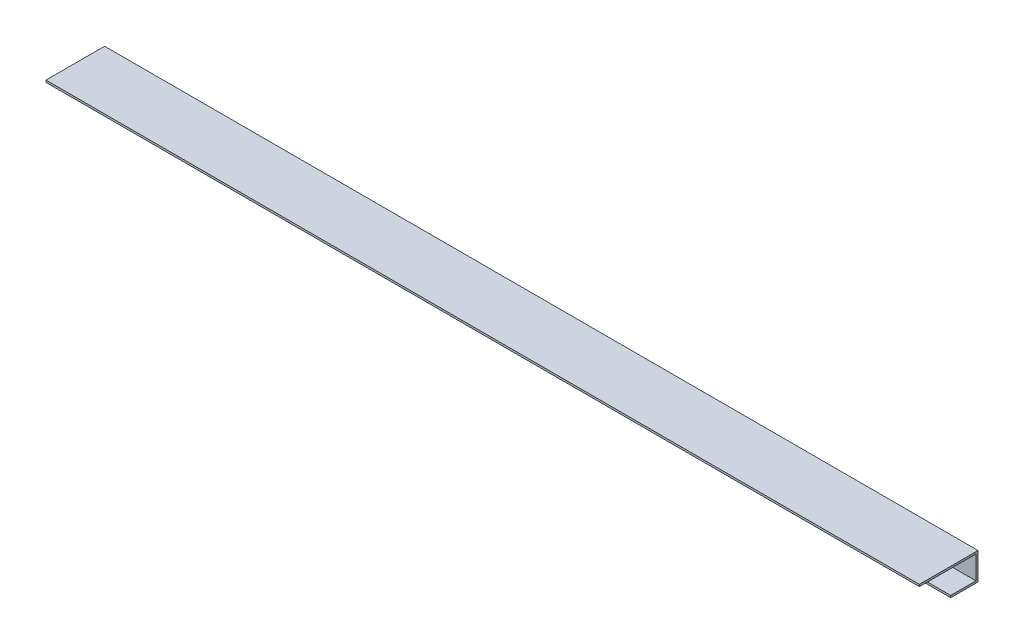
SolidWorks part; units mm, degrees
ref_plane "Front Plane" through (0, 0, 0) normal (0, 0, 1) x (1, 0, 0)
ref_plane "Top Plane" through (0, 0, 0) normal (0, 1, 0) x (1, 0, 0)
ref_plane "Right Plane" through (0, 0, 0) normal (1, 0, 0) x (0, 0, -1)
sketch "Sketch1" plane through (0, 0, 0) normal (1, 0, 0) x (0, 0, -1)
  line L0 (0, 0) -> (58, 0)
  line L1 (58, 0) -> (58, -27)
  line L2 (58, -27) -> (31, -27)
  line L3 (0, -2) -> (56, -2)
  line L4 (56, -2) -> (56, -25)
  line L5 (56, -25) -> (31, -25)
  line L6 (0, 0) -> (0, -2)
  line L7 (31, -25) -> (31, -27)
  dimension "D1" = 2
  dimension "D2" = 58
  dimension "D3" = 27
  dimension "D4" = 27
extrude "Boss-Extrude1" add sketch "Sketch1" along normal blind 864
equation "\"door_base_short7_R1_L_open_Single_width\"=864"
equation "\"D1@Boss-Extrude1\"=\"door_base_short7_R1_L_open_Single_width\""
equation "\"CarBeamWidth\"=700.0"
equation "\"WheelWidth\"=650.0"
equation "\"Wheel_FrontBoxDistance\"=1390.0"
equation "\"MetalSheet_3mm_length\"=5030.0"
equation "\"MetalSheet_3mm_width\"=1923.0"
equation "\"MetalSheet_3mm_FloorCut_L_length\"=1764.0"
equation "\"MetalSheet_3mm_FloorCut_L_disdance\"=1665.0"
equation "\"MetalSheet_3mm_FloorCut_R_length\"=1764.0"
equation "\"MetalSheet_3mm_FloorCut_R_disdance\"=1665.0"
equation "\"indoorHeight\"=1940.0"
equation "\"haveDoor_R\"=1"
equation "\"side_door_bottom_R_3mm_length\"=1934.0"
equation "\"1Bar_Side_RF_3mm_length\"=1493.0"
equation "\"1Bar_Side_RB_3mm_length\"=1493.0"
equation "\"DoorSeparator_RF_3mm_withHinge_toFrontDistance\"=1673.0"
equation "\"DoorSeparator_RF_3mm_withHinge_exist\"=1"
equation "\"DoorSeparator_RB_3mm_withHinge_toFrontDistance\"=3427.0"
equation "\"DoorSeparator_RB_3mm_withHinge_exist\"=1"
equation "\"Door_R1_L_open_Single_toFrontDistance\"=2547.5"
equation "\"Door_R1_L_open_Single_exist\"=1"
equation "\"door_base_long7_R1_L_open_Single_height\"=1890.0"
equation "\"door_base_short7_R1_L_open_Single_height\"=1890.0"
equation "\"Door_R1_R_open_Single_toFrontDistance\"=3422.0"
equation "\"Door_R1_R_open_Single_exist\"=1"
equation "\"door_base_long7_R1_R_open_Single_height\"=1890.0"
equation "\"door_base_short7_R1_R_open_Single_height\"=1890.0"
equation "\"door_base_short7_R1_R_open_Single_width\"=864"
equation "\"x\"=66.0"
equation "\"da\"=62.0"
equation "\"SquareTube_length\"=1923.0"
equation "\"channelSteel_length\"=5030.0"
equation "\"SquareTube_inFront_AvgDistance\"=285.0"
equation "\"SquareTube_inFront_TotalCount\"=5"
equation "\"SquareTube_inFront1_cutDepth50_R\"=0.5"
equation "\"SquareTube_inFront1_cutDepth50_L\"=0.5"
equation "\"SquareTube_inFront2_cutDepth50_R\"=0.5"
equation "\"SquareTube_inFront2_cutDepth50_L\"=0.5"
equation "\"SquareTube_inFront3_cutDepth50_R\"=0.5"
equation "\"SquareTube_inFront3_cutDepth50_L\"=0.5"
equation "\"SquareTube_inFront4_cutDepth50_R\"=0.5"
equation "\"SquareTube_inFront4_cutDepth50_L\"=0.5"
equation "\"SquareTube_inFront5_cutDepth50_R\"=50"
equation "\"SquareTube_inFront5_cutDepth50_L\"=50"
equation "\"SquareTube_inFront6_cutDepth50_R\"=50"
equation "\"SquareTube_inFront6_cutDepth50_L\"=50"
equation "\"SquareTube_inFront7_cutDepth50_R\"=50"
equation "\"SquareTube_inFront7_cutDepth50_L\"=50"
equation "\"SquareTube_inFront8_cutDepth50_R\"=50"
equation "\"SquareTube_inFront8_cutDepth50_L\"=50"
equation "\"SquareTube_inFront9_cutDepth50_R\"=50"
equation "\"SquareTube_inFront9_cutDepth50_L\"=50"
equation "\"SquareTube_inFront10_cutDepth50_R\"=50"
equation "\"SquareTube_inFront10_cutDepth50_L\"=50"
equation "\"SquareTube_inFront11_cutDepth50_R\"=50"
equation "\"SquareTube_inFront11_cutDepth50_L\"=50"
equation "\"SquareTube_inFront12_cutDepth50_R\"=50"
equation "\"SquareTube_inFront12_cutDepth50_L\"=50"
equation "\"SquareTube_inFront13_cutDepth50_R\"=50"
equation "\"SquareTube_inFront13_cutDepth50_L\"=50"
equation "\"SquareTube_inFront14_cutDepth50_R\"=50"
equation "\"SquareTube_inFront14_cutDepth50_L\"=50"
equation "\"SquareTube_inBack_AvgDistance\"=333.125"
equation "\"SquareTube_inBack_TotalCount\"=9"
equation "\"SquareTube_inBack1_cutDepth50_R\"=50"
equation "\"SquareTube_inBack1_cutDepth50_L\"=50"
equation "\"SquareTube_inBack2_cutDepth50_R\"=50"
equation "\"SquareTube_inBack2_cutDepth50_L\"=50"
equation "\"SquareTube_inBack3_cutDepth50_R\"=50"
equation "\"SquareTube_inBack3_cutDepth50_L\"=50"
equation "\"SquareTube_inBack4_cutDepth50_R\"=50"
equation "\"SquareTube_inBack4_cutDepth50_L\"=50"
equation "\"SquareTube_inBack5_cutDepth50_R\"=50"
equation "\"SquareTube_inBack5_cutDepth50_L\"=50"
equation "\"SquareTube_inBack6_cutDepth50_R\"=0.5"
equation "\"SquareTube_inBack6_cutDepth50_L\"=0.5"
equation "\"SquareTube_inBack7_cutDepth50_R\"=0.5"
equation "\"SquareTube_inBack7_cutDepth50_L\"=0.5"
equation "\"SquareTube_inBack8_cutDepth50_R\"=0.5"
equation "\"SquareTube_inBack8_cutDepth50_L\"=0.5"
